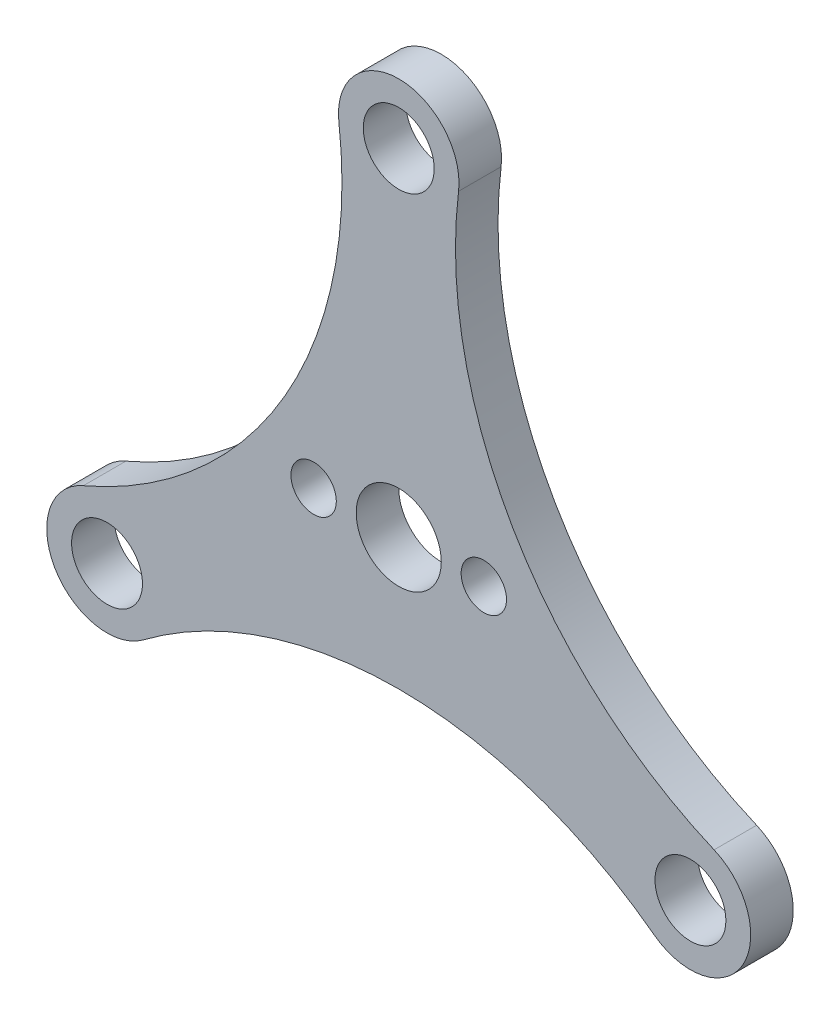
SolidWorks part; units mm, degrees
material "AISI 316 ｽﾃﾝﾚｽ鋼板 (SS)"
ref_plane "正面" through (0, 0, 0) normal (0, 0, 1) x (1, 0, 0)
ref_plane "平面" through (0, 0, 0) normal (0, 1, 0) x (1, 0, 0)
ref_plane "右側面" through (0, 0, 0) normal (1, 0, 0) x (0, 0, -1)
sketch "ｽｹｯﾁ1" plane through (0, 0, 0) normal (0, 0, 1) x (1, 0, 0)
  line L0 (0, 0) -> (0, 23.75) construction
  line L1 (0, 0) -> (20.5681, -11.875) construction
  line L2 (0, 0) -> (-20.5681, -11.875) construction
  line L3 (-6, 0) -> (6, 0) construction
  line L4 (0, 23.75) -> (-20.5681, -11.875) construction
  line L5 (-10.2841, 5.9375) -> (-34.0014, 19.6307) construction
  circle A0 centre (0, 23.75) radius 2.5
  circle A3 centre (0, 0) radius 3
  circle A4 centre (-6, 0) radius 1.6
  circle A5 centre (6, 0) radius 1.6
  circle A6 centre (20.5681, -11.875) radius 2.5 [skipped]
  circle A7 centre (-20.5681, -11.875) radius 2.5 [skipped]
  circle A8 centre (20.5681, -11.875) radius 2.5
  circle A9 centre (-20.5681, -11.875) radius 2.5
  arc A10 (-22.235, -7.9655) -> (-18.0159, -15.2733) centre (-20.5681, -11.875) ccw
  arc A11 (-22.235, -7.9655) -> (-4.2191, 23.2388) centre (-34.0014, 19.6307) ccw
  arc A12 (4.2191, 23.2388) -> (-4.2191, 23.2388) centre (0, 23.75) ccw
  arc A13 (4.2191, 23.2388) -> (22.235, -7.9655) centre (34.0014, 19.6307) ccw
  arc A14 (18.0159, -15.2733) -> (22.235, -7.9655) centre (20.5681, -11.875) ccw
  arc A15 (18.0159, -15.2733) -> (-18.0159, -15.2733) centre (0, -39.2614) ccw
  point P10 (0, 0)
  point P24 (0, 0)
  point P37 (0, 0)
  dimension "D1" = 5
  dimension "D4" = 6
  dimension "D6" = 3.2
  dimension "D8" = 4.25
  dimension "D9" = 30
  dimension "D2" = 23.75
  dimension "D5" = 12
  dimension "D3" = 3
  dimension "D7" = 3
  dimension "D10" = 3
extrude "ﾎﾞｽ - 押し出し1" add sketch "ｽｹｯﾁ1" along normal blind 3
